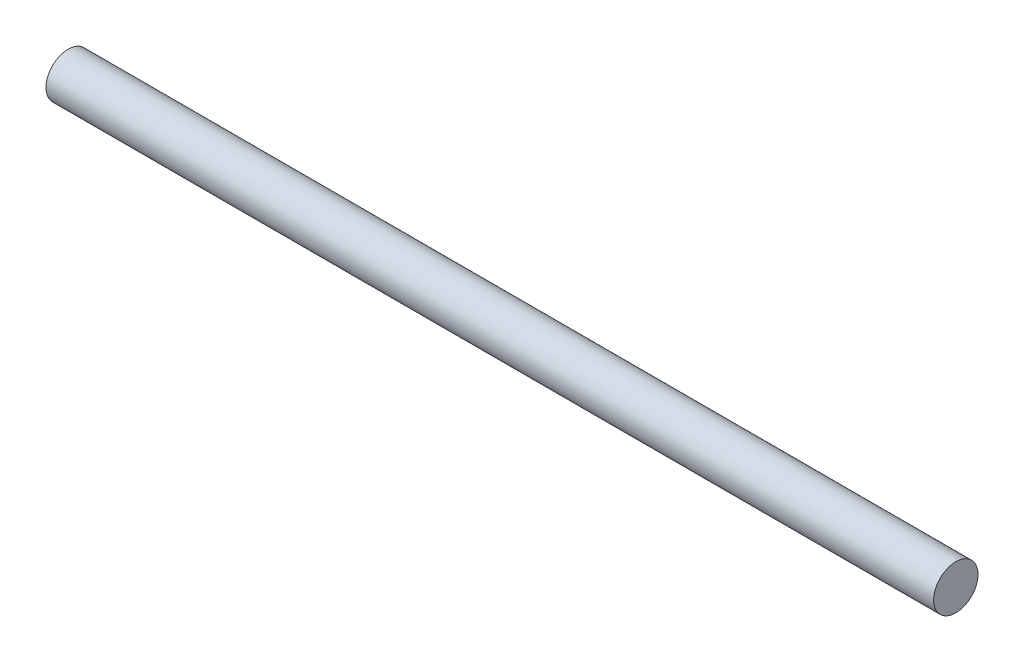
SolidWorks part; units mm, degrees
ref_plane "Front Plane" through (0, 0, 0) normal (0, 0, 1) x (1, 0, 0)
ref_plane "Top Plane" through (0, 0, 0) normal (0, 1, 0) x (1, 0, 0)
ref_plane "Right Plane" through (0, 0, 0) normal (1, 0, 0) x (0, 0, -1)
sketch "Sketch1" plane through (0, 0, 0) normal (1, 0, 0) x (0, 0, -1)
  circle A0 centre (0, 0) radius 2.54
  dimension "D1" = 5.08
extrude "Boss-Extrude1" add sketch "Sketch1" along normal blind 101.6
